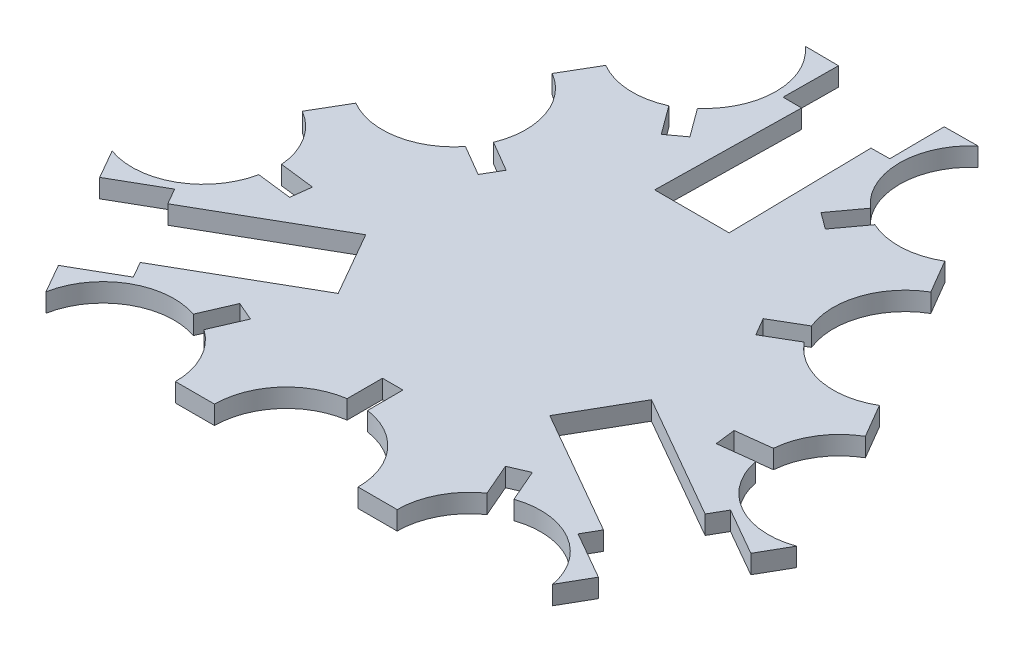
SolidWorks part; units mm, degrees
ref_plane "Plan de face" through (0, 0, 0) normal (0, 0, 1) x (1, 0, 0)
ref_plane "Plan de dessus" through (0, 0, 0) normal (0, 1, 0) x (1, 0, 0)
ref_plane "Plan de droite" through (0, 0, 0) normal (1, 0, 0) x (0, 0, -1)
sketch "Esquisse2" plane through (0, 0, 0) normal (0, 1, 0) x (1, 0, 0)
  line L0 (-47.3703, 105.7135) -> (210.0286, 105.7135) construction
  line L1 (15.954, 129.8427) -> (273.3529, 129.8427) construction
  line L2 (36.4131, 132.9666) -> (76.4131, 132.9666)
  line L3 (56.4131, 132.9666) -> (56.4131, -156.9927) construction
  line L4 (133.1685, 34.4753) -> (113.2687, -0.2233)
  line L5 (-20.3423, 34.4753) -> (-0.4425, -0.2233)
  line L6 (-10.3924, 17.126) -> (219.3388, 148.8778) construction
  line L7 (123.2186, 17.126) -> (-67.8998, 126.7332) construction
  line L8 (113.2687, -0.2233) -> (180.8548, -38.9842)
  line L9 (180.8548, -38.9842) -> (175.8799, -47.6589)
  line L10 (175.8799, -47.6589) -> (201.4701, -62.335)
  line L11 (201.4701, -62.335) -> (192.5152, -77.9494)
  line L12 (142.5467, -48.7781) -> (135.005, -31.339)
  line L13 (135.005, -31.339) -> (124.9087, -35.7053)
  line L14 (124.9087, -35.7053) -> (132.4504, -53.1444)
  line L15 (115.9795, -84.9522) -> (94.9795, -84.9522)
  line L16 (50.9131, -27.78) -> (61.9131, -27.78)
  line L17 (61.9131, -27.78) -> (61.9131, -46.78)
  line L18 (-0.4425, -0.2233) -> (-68.0286, -38.9842)
  line L19 (-68.0286, -38.9842) -> (-63.0536, -47.6589)
  line L20 (-63.0536, -47.6589) -> (-88.6439, -62.335)
  line L21 (-88.6439, -62.335) -> (-79.689, -77.9494)
  line L22 (-29.7205, -48.7781) -> (-22.1788, -31.339)
  line L23 (-22.1788, -31.339) -> (-12.0825, -35.7053)
  line L24 (-12.0825, -35.7053) -> (-19.6242, -53.1444)
  line L25 (-3.1532, -84.9522) -> (17.8468, -84.9522)
  line L26 (50.9131, -27.78) -> (50.9131, -46.78)
  line L27 (36.4131, 132.9666) -> (37.7568, 210.531)
  line L28 (37.7568, 210.531) -> (27.7571, 210.6177)
  line L29 (27.7571, 210.6177) -> (28.0129, 240.1166)
  line L30 (28.0129, 240.1166) -> (10.0135, 240.2726)
  line L31 (9.958, 182.4124) -> (21.2016, 167.0963)
  line L32 (21.2016, 167.0963) -> (12.3343, 160.5869)
  line L33 (12.3343, 160.5869) -> (1.0908, 175.903)
  line L34 (-34.681, 177.7494) -> (-45.2859, 159.6238)
  line L35 (-12.6377, 102.2118) -> (-29.0371, 111.8067)
  line L36 (-18.1927, 92.7175) -> (-12.6377, 102.2118)
  line L37 (-18.1927, 92.7175) -> (-34.592, 102.3124)
  line L38 (-94.8425, 74.9234) -> (-84.2376, 93.0489)
  line L39 (-56.8457, 42.3469) -> (-75.7063, 44.6441)
  line L40 (-58.1757, 31.4276) -> (-56.8457, 42.3469)
  line L41 (-77.0363, 33.7248) -> (-58.1757, 31.4276)
  line L42 (-118.4936, -10.287) -> (-127.4485, 5.3274)
  line L43 (-92.9034, 4.3891) -> (-118.4936, -10.287)
  line L44 (-87.9284, -4.2856) -> (-92.9034, 4.3891)
  line L45 (-20.3423, 34.4753) -> (-87.9284, -4.2856)
  line L46 (76.4131, 132.9666) -> (75.0695, 210.531)
  line L47 (75.0695, 210.531) -> (85.0691, 210.6177)
  line L48 (85.0691, 210.6177) -> (84.8134, 240.1166)
  line L49 (84.8134, 240.1166) -> (102.8127, 240.2726)
  line L50 (102.8682, 182.4124) -> (91.6247, 167.0963)
  line L51 (91.6247, 167.0963) -> (100.4919, 160.5869)
  line L52 (100.4919, 160.5869) -> (111.7354, 175.903)
  line L53 (147.5072, 177.7494) -> (158.1121, 159.6238)
  line L54 (125.464, 102.2118) -> (141.8633, 111.8067)
  line L55 (125.464, 102.2118) -> (131.0189, 92.7175)
  line L56 (131.0189, 92.7175) -> (147.4182, 102.3124)
  line L57 (207.6688, 74.9234) -> (197.0638, 93.0489)
  line L58 (169.6719, 42.3469) -> (188.5325, 44.6441)
  line L59 (171.0019, 31.4276) -> (169.6719, 42.3469)
  line L60 (189.8625, 33.7248) -> (171.0019, 31.4276)
  line L61 (231.3199, -10.287) -> (240.2748, 5.3274)
  line L62 (205.7296, 4.3891) -> (231.3199, -10.287)
  line L63 (200.7546, -4.2856) -> (205.7296, 4.3891)
  line L64 (133.1685, 34.4753) -> (200.7546, -4.2856)
  arc A0 (192.5152, -77.9494) -> (142.5467, -48.7781) centre (154.9278, -84.9522) ccw
  arc A1 (132.4504, -53.1444) -> (115.9795, -84.9522) centre (154.9278, -84.9522) ccw
  arc A2 (94.9795, -84.9522) -> (61.9131, -46.78) centre (56.4131, -84.9522) ccw
  arc A3 (-79.689, -77.9494) -> (-29.7205, -48.7781) centre (-42.1015, -84.9522) cw
  arc A4 (-19.6242, -53.1444) -> (-3.1532, -84.9522) centre (-42.1015, -84.9522) cw
  arc A5 (17.8468, -84.9522) -> (50.9131, -46.78) centre (56.4131, -84.9522) cw
  arc A6 (10.0135, 240.2726) -> (9.958, 182.4124) centre (-15.0122, 211.3665) cw
  arc A7 (1.0908, 175.903) -> (-34.681, 177.7494) centre (-15.0122, 211.3665) cw
  arc A8 (-45.2859, 159.6238) -> (-29.0371, 111.8067) centre (-64.7618, 126.3364) cw
  arc A9 (-84.2376, 93.0489) -> (-34.592, 102.3124) centre (-64.7618, 126.3364) ccw
  arc A10 (-75.7063, 44.6441) -> (-94.8425, 74.9234) centre (-114.5113, 41.3063) ccw
  arc A11 (-127.4485, 5.3274) -> (-77.0363, 33.7248) centre (-114.5113, 41.3063) ccw
  arc A12 (102.8127, 240.2726) -> (102.8682, 182.4124) centre (127.8385, 211.3665) ccw
  arc A13 (111.7354, 175.903) -> (147.5072, 177.7494) centre (127.8385, 211.3665) ccw
  arc A14 (158.1121, 159.6238) -> (141.8633, 111.8067) centre (177.588, 126.3364) ccw
  arc A15 (197.0638, 93.0489) -> (147.4182, 102.3124) centre (177.588, 126.3364) cw
  arc A16 (188.5325, 44.6441) -> (207.6688, 74.9234) centre (227.3375, 41.3063) cw
  arc A17 (240.2748, 5.3274) -> (189.8625, 33.7248) centre (227.3375, 41.3063) cw
  point P27 (0, 0)
  point P31 (0, 0)
  point P32 (0, 0)
  point P33 (0, 0)
  point P34 (0, 0)
  point P35 (0, 0)
  point P37 (133.1685, -53.6661)
  point P38 (132.4581, -53.7672)
  point P39 (0, 0)
  point P40 (142.5467, -48.7781)
  point P41 (132.7507, -53.7818)
  point P42 (0, 0)
  point P43 (190.14, -76.5873)
  point P44 (190.14, -76.5873)
  point P45 (0, 0)
  point P46 (192.5152, -77.9494)
  point P60 (56.4131, -27.78)
  point P88 (0, 0)
  point P117 (0, 0)
  point P118 (0, 0)
  point P119 (0, 0)
  point P120 (0, 0)
  dimension "D10" = 19
  dimension "D8" = 21
  dimension "D1" = 40
  dimension "D2" = 40
  dimension "D3" = 10
  dimension "D4" = 29.5
  dimension "D5" = 18
  dimension "D6" = 11
  dimension "D7" = 19
  dimension "D9" = 5.5
sketch "Esquisse3" plane through (0, 0, 0) normal (0, 1, 0) x (1, 0, 0)
  line L0 (-28.165, -48.9935) -> (-19.511, -32.612)
  line L1 (113.727, -0.0529) -> (123.8868, 17.1743)
  line L2 (113.727, -0.0529) -> (180.6451, -39.518)
  line L3 (-19.511, -32.612) -> (-10.2038, -37.5287)
  line L4 (58.4553, 57.7716) -> (58.4553, 272.2226) construction
  line L5 (180.6451, -39.518) -> (175.7471, -47.8231)
  line L6 (58.4553, 57.7716) -> (228.5305, -47.7523) construction
  line L7 (58.4553, 57.7716) -> (-156.9606, -69.5184) construction
  line L8 (175.7471, -47.8231) -> (201.649, -63.0988)
  line L9 (201.649, -63.0988) -> (192.454, -78.6902)
  line L10 (142.8705, -48.751) -> (133.7344, -32.2457)
  line L11 (133.7344, -32.2457) -> (124.4882, -37.3637)
  line L12 (124.4882, -37.3637) -> (133.7398, -54.0775)
  line L13 (116.4349, -85.5841) -> (95.1286, -85.5841)
  line L14 (62.7528, -47.4324) -> (62.7528, -29.0459)
  line L15 (62.7528, -29.0459) -> (52.1929, -29.0459)
  line L16 (52.1929, -29.0459) -> (52.1929, -48.4796)
  line L17 (19.1123, -85.5841) -> (-2.9302, -85.5841)
  line L18 (-10.2038, -37.5287) -> (-18.946, -54.0773)
  line L21 (-79.5745, -78.3367) -> (-88.5785, -63.0988)
  line L22 (-88.5785, -63.0988) -> (-62.5129, -47.6968)
  line L23 (-62.5129, -47.6968) -> (-67.5011, -39.255)
  line L24 (-67.5011, -39.255) -> (0, 0)
  line L25 (0, 0) -> (-10.0544, 17.289)
  line L38 (-58.3275, 33.0789) -> (-58.1442, 43.602)
  arc A0 (192.454, -78.6902) -> (142.8705, -48.751) centre (154.2885, -85.8694) ccw
  arc A1 (133.7398, -54.0775) -> (116.4349, -85.5841) centre (154.2885, -85.8694) ccw
  arc A2 (95.1286, -85.5841) -> (62.7528, -47.4324) centre (56.4616, -85.5841) ccw
  arc A3 (52.1929, -48.4796) -> (19.1123, -85.5841) centre (56.4616, -85.5841) ccw
  arc A4 (-2.9302, -85.5841) -> (-18.946, -54.0773) centre (-41.4871, -85.3596) ccw
  arc A5 (-28.165, -48.9935) -> (-79.5745, -78.3367) centre (-41.4871, -85.3596) ccw
  point P13 (58.4553, 57.7716)
  dimension "D1" = 20
  dimension "D2" = 20
extrude "Boss.-Extru.1" add sketch "Esquisse2" along normal blind 10
